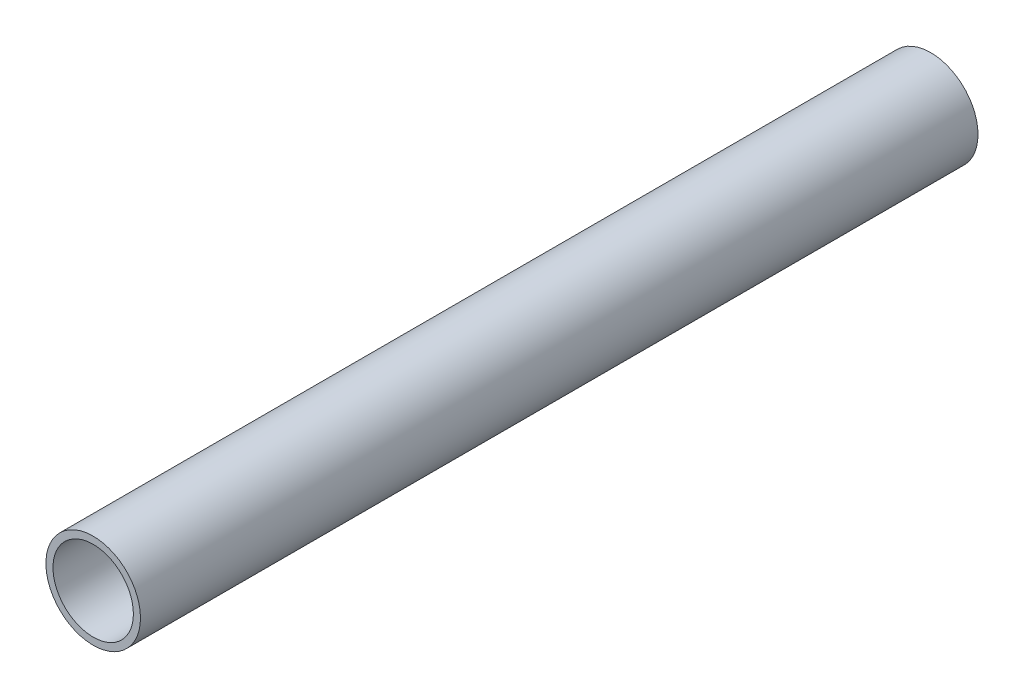
SolidWorks part; units mm, degrees
material "Aço carbono simples"
ref_plane "Plano frontal" through (0, 0, 0) normal (0, 0, 1) x (1, 0, 0)
ref_plane "Plano superior" through (0, 0, 0) normal (0, 1, 0) x (1, 0, 0)
ref_plane "Plano direito" through (0, 0, 0) normal (1, 0, 0) x (0, 0, -1)
sketch "Esboço1" plane through (0, 0, 0) normal (0, 0, 1) x (1, 0, 0)
  circle A0 centre (0, 0) radius 12.7
  circle A1 centre (0, 0) radius 10.8
  dimension "D1" = 25.4
  dimension "D2" = 1.9
extrude "Ressalto-extrusão1" add sketch "Esboço1" along normal blind 225
